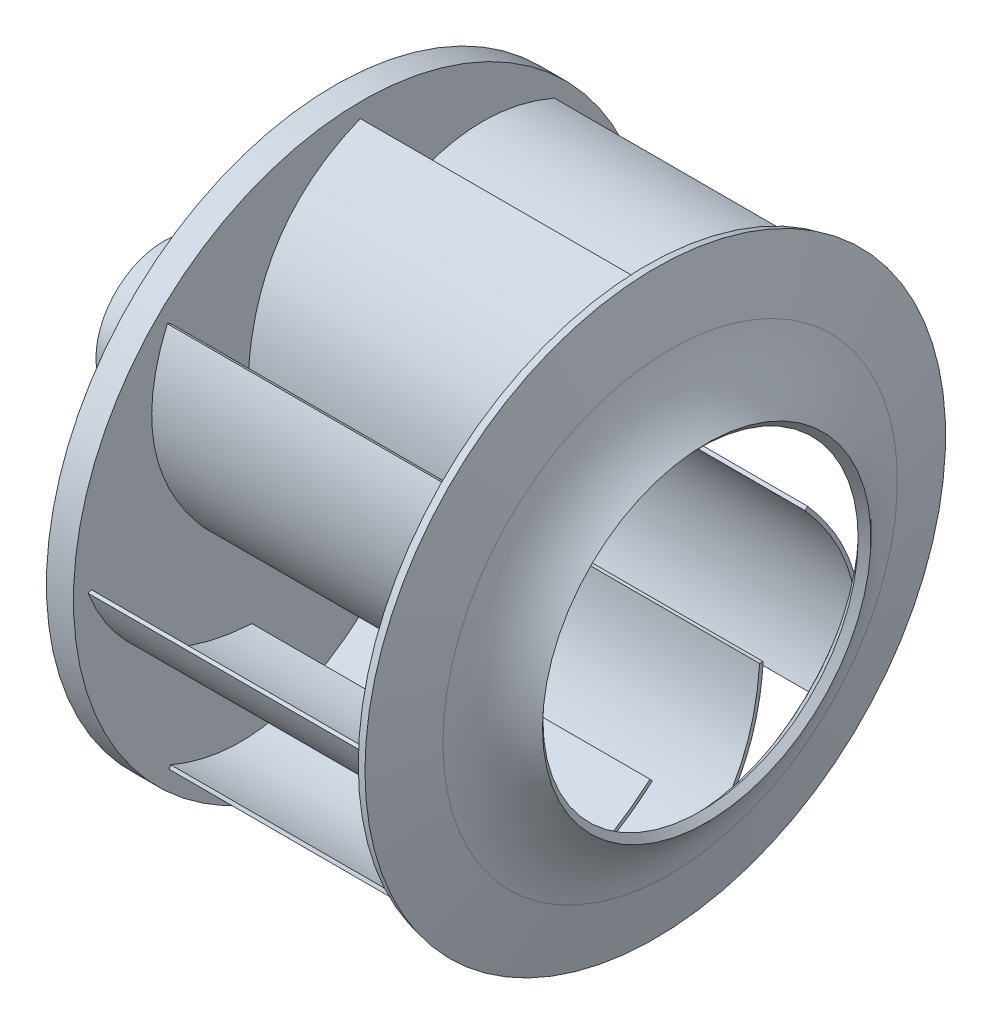
SolidWorks part; units mm, degrees
material "Plain Carbon Steel"
ref_plane "Front Plane" through (0, 0, 0) normal (0, 0, 1) x (1, 0, 0)
ref_plane "Top Plane" through (0, 0, 0) normal (0, 1, 0) x (1, 0, 0)
ref_plane "Right Plane" through (0, 0, 0) normal (1, 0, 0) x (0, 0, -1)
sketch "Sketch1" plane through (0, 0, 0) normal (1, 0, 0) x (0, 0, -1)
  circle A0 centre (0, 0) radius 32
  circle A1 centre (0, 0) radius 2.5
  dimension "D1" = 64
  dimension "D2" = 5
extrude "Boss-Extrude1" add sketch "Sketch1" along normal blind 3
sketch "Sketch2" plane through (0, 0, 0) normal (-1, 0, 0) x (0, 0, 1)
  circle A0 centre (0, 0) radius 7.5
  circle A3 centre (0, 0) radius 4.5
  dimension "D1" = 15
  dimension "D3" = 9
extrude "Boss-Extrude2" add sketch "Sketch2" along normal blind 19
sketch "Sketch3" plane through (-19, 0, 0) normal (-1, 0, 0) x (0, 0, 1)
  line L1 (2.8284, 3.5) -> (-2.8284, 3.5)
  line L2 (2.8284, 3.5) -> (2.8284, 4.5)
  line L3 (2.8284, 4.5) -> (-2.8284, 4.5)
  line L4 (-2.8284, 3.5) -> (-2.8284, 4.5)
  circle A0 centre (0, 0) radius 4.5 construction
  circle A1 centre (0, 0) radius 4.5 construction
  point P8 (0, 4.5)
  dimension "D1" = 1
extrude "Boss-Extrude3" add sketch "Sketch3" against normal up to next
sketch "Sketch4" plane through (3, 0, 0) normal (1, 0, 0) x (0, 0, -1)
  line L0 (-17.2132, -24) -> (-17.2132, 24) construction
  line L1 (0, 0) -> (-17.2132, 0) construction
  line L2 (-21.5806, 21.3713) -> (-21.2132, 21.2132)
  line L3 (-17.5139, -0.2637) -> (-17.2132, 0)
  line L4 (0, 0) -> (-21.2132, 21.2132) construction
  spline S0 degree 2 poles (-17.2132, 0) (-26.0204, 10.0425) (-21.2132, 21.2132) knots 0 0 0 1 1 1
  spline S1 degree 1 poles (-17.5139, -0.2637) (-21.5806, 21.3713) knots 0 0 1 1 construction
  spline S2 degree 3 poles (-17.5139, -0.2637) (-17.8787, 0.1522) (-18.596, 1.014) (-19.8647, 2.7245) (-21.1924, 4.8996) (-22.3531, 7.5499) (-23.0824, 10.2439) (-23.3765, 12.9772) (-23.2353, 15.7439) (-22.7544, 18.0776) (-22.157, 19.9512) (-21.7811, 20.9055) (-21.5806, 21.3713) knots 0 0 0 0 0.0625 0.125 0.25 0.375 0.5 0.625 0.75 0.875 0.9375 1 1 1 1
  point P6 (-17.2132, 0)
  dimension "D2" = 4
  dimension "D4" = 0.4
  dimension "D1" = 30
  dimension "D3" = 45
extrude "Boss-Extrude4" add sketch "Sketch4" along normal blind 32
pattern_circular "CirPattern1" count 8 over 360 about axis through (3, 0, 0) along (-1, 0, 0) of "Boss-Extrude4"
sketch "Sketch5" plane through (0, 0, 0) normal (0, 0, 1) x (1, 0, 0)
  line L0 (1.65, 0) -> (-1.65, 0) construction
  line L1 (36.2694, 25) -> (34.6152, 32)
  line L5 (37.2426, 25.23) -> (35.5884, 32.23)
  line L6 (41.2987, 18.23) -> (40.6152, 17.5)
  line L7 (35.5884, 32.23) -> (34.6152, 32)
  line L8 (-14.3578, 0) -> (45.4165, 0) construction
  arc A0 (40.6152, 17.5) -> (36.2694, 25) centre (50.8673, 28.4496) cw
  arc A1 (41.2987, 18.23) -> (37.2426, 25.23) centre (50.8673, 28.4496) cw
  dimension "D1" = 15
  dimension "D2" = 32
  dimension "D3" = 25
  dimension "D4" = 17.5
  dimension "D6" = 6
  dimension "D7" = 1
revolve "Revolve1" add sketch "Sketch5" angle 360 about L8
sketch "Sketch6" plane through (0, 0, 0) normal (-1, 0, 0) x (0, 0, 1)
  line L0 (-2.8284, 3.5) -> (2.8284, 3.5) construction
  line L1 (-2.8284, 3.5) -> (2.8284, 3.5)
  arc A0 (-2.8284, 3.5) -> (2.8284, 3.5) centre (0, 0) ccw construction
  arc A1 (-2.8284, 3.5) -> (2.8284, 3.5) centre (0, 0) ccw
  circle A2 centre (0, 0) radius 2.5 construction
  circle A3 centre (0, 0) radius 2.5
extrude "Boss-Extrude5" add sketch "Sketch6" along normal blind 7
